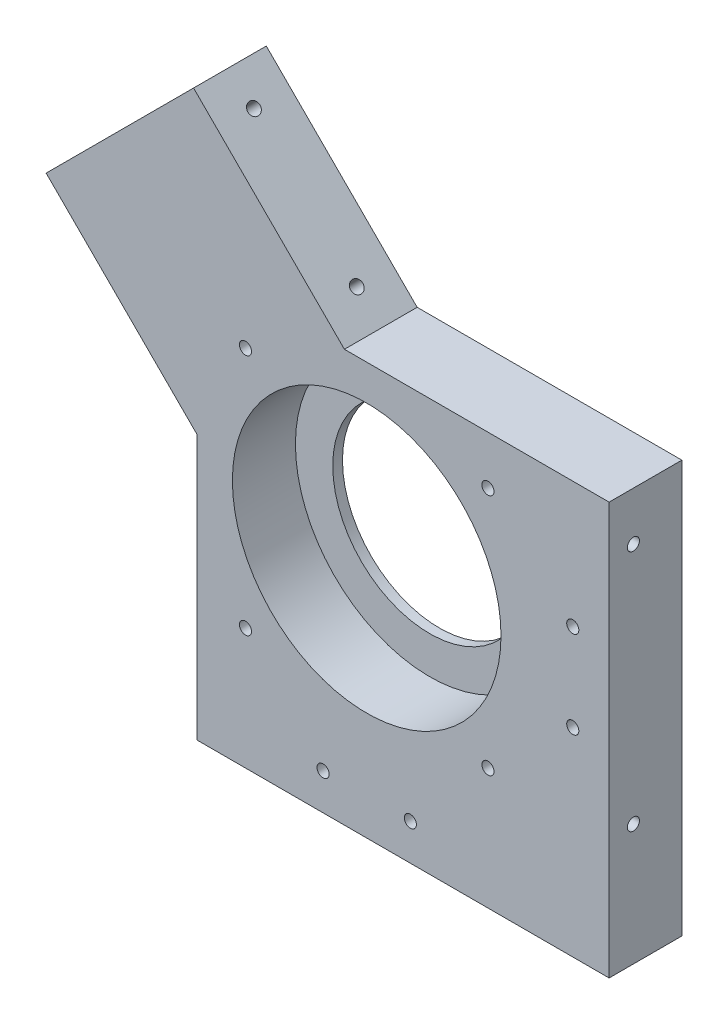
SolidWorks part; units mm, degrees
ref_plane "Front Plane" through (0, 0, 0) normal (0, 0, 1) x (1, 0, 0)
ref_plane "Top Plane" through (0, 0, 0) normal (0, 1, 0) x (1, 0, 0)
ref_plane "Right Plane" through (0, 0, 0) normal (1, 0, 0) x (0, 0, -1)
sketch "Sketch1" plane through (0, 0, 0) normal (0, 0, 1) x (1, 0, 0)
  line L0 (-50.9117, 50.9117) -> (0, 0) construction
  line L1 (50, 35) -> (50, -50)
  line L2 (50, -50) -> (-35, -50)
  line L4 (-50.9117, 50.9117) -> (-35.7089, 66.1145)
  line L5 (-50.9117, 50.9117) -> (-66.1145, 35.7089)
  line L7 (-4.5944, 35) -> (50, 35)
  line L11 (-25, 25) -> (25, 25) construction
  line L12 (25, 25) -> (25, -25) construction
  line L13 (25, -25) -> (-25, -25) construction
  line L14 (-25, -25) -> (-25, 25) construction
  line L19 (-35.7089, 66.1145) -> (-4.5944, 35)
  line L20 (-66.1145, 35.7089) -> (-35, 4.5944)
  line L22 (-35, -50) -> (-35, 4.5944)
  line L23 (42.5, 9) -> (42.5, -9) construction
  line L24 (-9, -42.5) -> (9, -42.5) construction
  circle A0 centre (0, 0) radius 27.7
  circle A1 centre (-25, 25) radius 1.25
  circle A2 centre (25, 25) radius 1.25
  circle A3 centre (25, -25) radius 1.25
  circle A4 centre (-25, -25) radius 1.25
  circle A5 centre (42.5, 9) radius 1.25
  circle A6 centre (42.5, -9) radius 1.25
  circle A7 centre (9, -42.5) radius 1.25
  circle A8 centre (-9, -42.5) radius 1.25
  dimension "D3" = 55.4
  dimension "D16" = 2.5
  dimension "D17" = 2.5
  dimension "D18" = 2.5
  dimension "D19" = 2.5
  dimension "D22" = 2.5
  dimension "D23" = 2.5
  dimension "D28" = 2.5
  dimension "D29" = 2.5
  dimension "D2" = 50
  dimension "D4" = 50
  dimension "D5" = 72
  dimension "D6" = 21.5
  dimension "D7" = 21.5
  dimension "D8" = 35
  dimension "D9" = 135
  dimension "D10" = 18
  dimension "D11" = 44.0025
  dimension "D12" = 35
  dimension "D13" = 50
  dimension "D14" = 25
  dimension "D15" = 25
  dimension "D20" = 135
  dimension "D21" = 9
  dimension "D24" = 7.5
  dimension "D25" = 18
  dimension "D26" = 9
  dimension "D27" = 7.5
extrude "Boss-Extrude1" add sketch "Sketch1" along normal blind 15
sketch "Sketch2" plane through (-15.2028, -15.2028, 0) normal (-0.7071, -0.7071, 0) x (0, 0, 1)
  line L1 (15, 72) -> (0, 72) construction
  line L2 (0, 72) -> (0, 27.9975) construction
  circle A0 centre (7.5, 65) radius 1.25
  circle A1 centre (7.5, 35) radius 1.25
  dimension "D1" = 2.5
  dimension "D2" = 2.5
  dimension "D3" = 7.5
  dimension "D4" = 7.5
  dimension "D5" = 7
  dimension "D6" = 30
extrude "Cut-Extrude1" cut sketch "Sketch2" against normal up to next
sketch "Sketch6" plane through (0, 0, 0) normal (0, 0, -1) x (-1, 0, 0)
  circle A0 centre (0, 0) radius 27.7
  circle A1 centre (0, 0) radius 20
  dimension "D1" = 40
extrude "Boss-Extrude4" add sketch "Sketch6" against normal blind 2
sketch "Sketch7" plane through (0, -50, 0) normal (0, -1, 0) x (1, 0, 0)
  line L0 (50, 15) -> (50, 0) construction
  line L1 (-35, 15) -> (50, 15) construction
  circle A0 centre (25, 10) radius 1.25
  circle A1 centre (-25, 10) radius 1.25
  dimension "D3" = 2.5
  dimension "D4" = 2.5
  dimension "D1" = 25
  dimension "D2" = 50
  dimension "D5" = 5
  dimension "D6" = 5
extrude "Cut-Extrude2" cut sketch "Sketch7" against normal blind 15
sketch "Sketch8" plane through (50, 0, 0) normal (1, 0, 0) x (0, 0, -1)
  line L0 (-15, -50) -> (-15, 35) construction
  line L1 (-15, -50) -> (0, -50) construction
  circle A0 centre (-10, -25) radius 1.25
  circle A1 centre (-10, 25) radius 1.25
  dimension "D1" = 2.5
  dimension "D2" = 2.5
  dimension "D3" = 5
  dimension "D4" = 5
  dimension "D5" = 25
  dimension "D6" = 50
extrude "Cut-Extrude3" cut sketch "Sketch8" against normal blind 15
